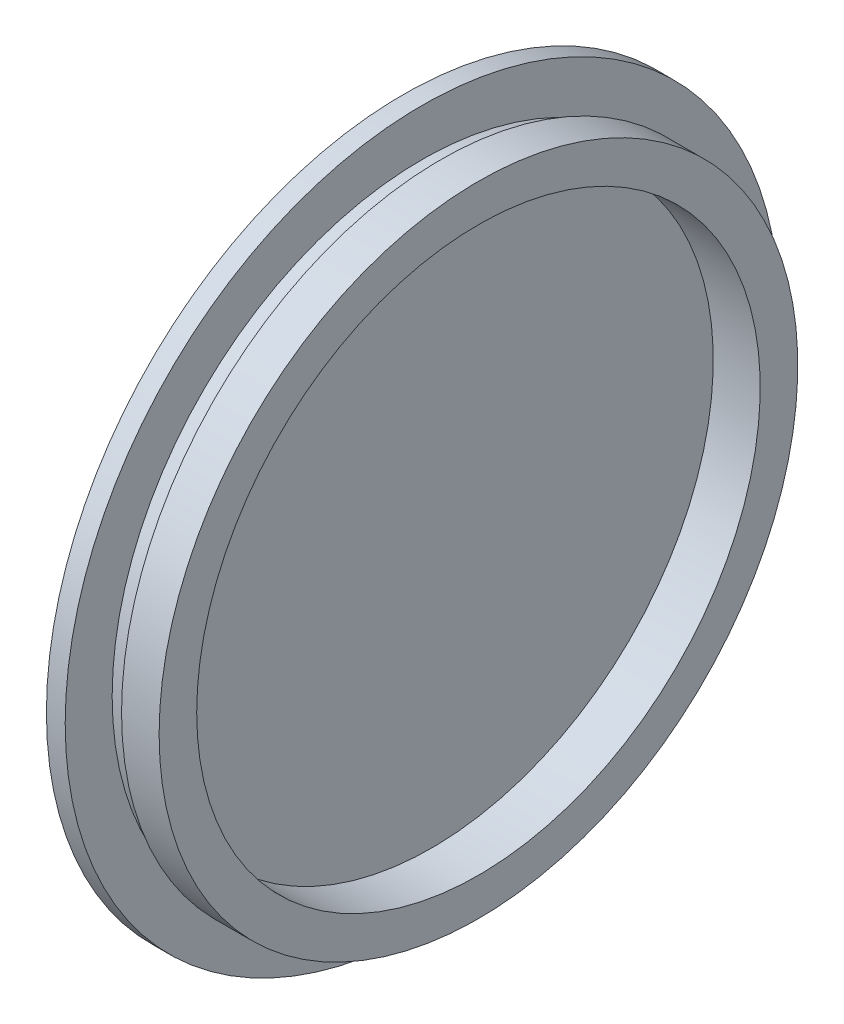
SolidWorks part; units mm, degrees
ref_plane "Front Plane" through (0, 0, 0) normal (0, 0, 1) x (1, 0, 0)
ref_plane "Top Plane" through (0, 0, 0) normal (0, 1, 0) x (1, 0, 0)
ref_plane "Right Plane" through (0, 0, 0) normal (1, 0, 0) x (0, 0, -1)
sketch "Sketch1" plane through (0, 0, 0) normal (0, 0, 1) x (1, 0, 0)
  line L0 (0, 19) -> (0, 0) construction
  line L1 (0, 0) -> (4, 0) construction
  line L2 (0, 19) -> (1, 19)
  line L3 (1, 19) -> (1, 16.5)
  line L4 (1, 16.5) -> (2, 16.5)
  line L5 (2, 16.5) -> (2, 17)
  line L6 (2, 17) -> (4, 17)
  line L7 (4, 17) -> (4, 15)
  line L8 (1.5, 0) -> (0, 0)
  line L9 (0, 0) -> (0, 19)
  line L10 (1.5, 0) -> (1.5, 15)
  line L11 (1.5, 15) -> (4, 15)
  dimension "D1" = 38
  dimension "D2" = 1.5
  dimension "D3" = 1
  dimension "D4" = 4
  dimension "D5" = 0.5
  dimension "D6" = 34
  dimension "D7" = 1
  dimension "D8" = 30
revolve "Revolve1" add sketch "Sketch1" angle 360 about L1
sketch "Sketch2" plane through (0, 0, 0) normal (-1, 0, 0) x (0, 0, 1)
  line L0 (0, 19) -> (0, -19) construction
  line L1 (-19, 0) -> (19, 0) construction
  circle A1 centre (-10, 0) radius 1
  circle A2 centre (0, 10) radius 1
  circle A3 centre (10, 0) radius 1
  circle A4 centre (0, -10) radius 1
  circle A5 centre (0, 0) radius 19 construction
  dimension "D1" = 20
  dimension "D3" = 2
  dimension "D2" = 20
extrude "Cut-Extrude1" cut sketch "Sketch2" against normal blind 1
